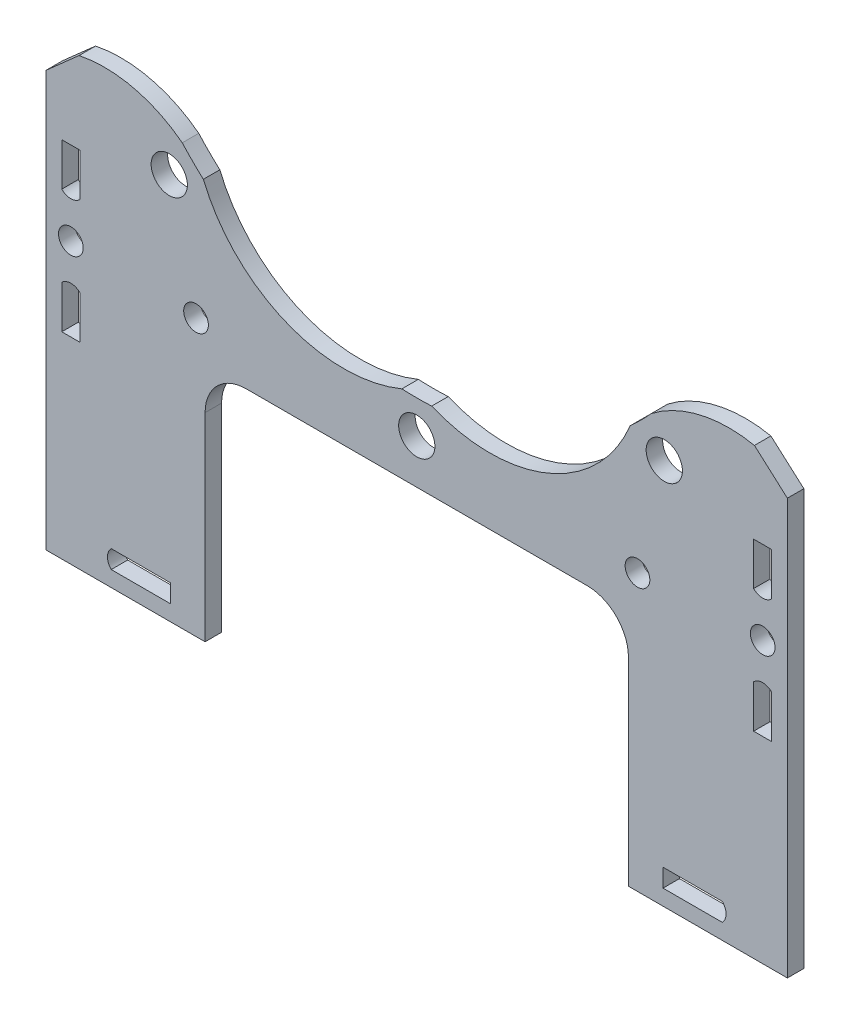
SolidWorks part; units mm, degrees
ref_plane "前视基准面" through (0, 0, 0) normal (0, 0, 1) x (1, 0, 0)
ref_plane "上视基准面" through (0, 0, 0) normal (0, 1, 0) x (1, 0, 0)
ref_plane "右视基准面" through (0, 0, 0) normal (1, 0, 0) x (0, 0, -1)
sketch "草图3" plane through (0, 0, 0) normal (0, 0, 1) x (1, 0, 0)
  line L0 (-37, -21.9902) -> (-37, -22.0902) construction
  line L2 (-41, -23.9902) -> (-42, -23.9902)
  line L5 (-37, -19.9902) -> (-30, -19.9902) construction
  line L6 (-37, -19.9902) -> (-37, -21.9902) construction
  line L7 (-37, -21.9902) -> (-30, -21.9902) construction
  line L8 (-30, -19.9902) -> (-30, -21.9902) construction
  line L9 (-37, -22.0902) -> (-37.1, -22.0902) construction
  line L11 (30, -19.9902) -> (37, -19.9902) construction
  line L12 (30, -19.9902) -> (30, -21.9902) construction
  line L13 (30, -21.9902) -> (37, -21.9902) construction
  line L14 (37, -19.9902) -> (37, -21.9902) construction
  line L19 (-37.1, -22.0902) -> (-29.9, -22.0902)
  line L21 (-37.1, -19.8902) -> (-29.9, -19.8902)
  line L22 (-29.9, -22.0902) -> (-29.9, -19.8902)
  line L23 (29.9, -22.0902) -> (29.9, -19.8902)
  line L24 (37.1, -22.0902) -> (29.9, -22.0902)
  line L26 (37.1, -19.8902) -> (29.9, -19.8902)
  line L34 (-25.7, -23.9902) -> (-25.7, -19.8902)
  line L39 (-41, 0.0098) -> (-44, 0.0098) construction
  line L40 (-44, 0.0098) -> (-44, 5.0098) construction
  line L41 (-44, 5.0098) -> (-41, 5.0098) construction
  line L55 (-41, 15.0098) -> (-44, 15.0098) construction
  line L56 (-44, 15.0098) -> (-44, 20.0098) construction
  line L57 (-44, 20.0098) -> (-41, 20.0098) construction
  line L79 (-41, -23.9902) -> (-25.7, -23.9902)
  line L82 (0, 10.5098) -> (0, 5.0098) construction
  line L87 (-25.7, -19.8902) -> (-25.7, -18.8902)
  line L88 (41, -23.9902) -> (25.7, -23.9902)
  line L89 (25.7, -19.8902) -> (25.7, -18.8902)
  line L90 (25.7, -23.9902) -> (25.7, -19.8902)
  line L91 (-25.7, -18.8902) -> (25.7, -18.8902) construction
  line L97 (-42, 0.0098) -> (-42, 5.0098) construction
  line L98 (-42, 15.0098) -> (-42, 20.0098) construction
  line L100 (-43.1, 5.1098) -> (-43.1, -0.0902)
  line L101 (-43.1, -0.0902) -> (-40.9, -0.0902)
  line L102 (-40.9, 5.1098) -> (-40.9, -0.0902)
  line L103 (-43.1, 5.1098) -> (-40.9, -0.0902) construction
  line L104 (-43.1, -0.0902) -> (-40.9, 5.1098) construction
  line L106 (-43.1, 20.1098) -> (-40.9, 20.1098)
  line L107 (-43.1, 20.1098) -> (-43.1, 14.9098)
  line L109 (-40.9, 20.1098) -> (-40.9, 14.9098)
  line L110 (-43.1, 20.1098) -> (-40.9, 14.9098) construction
  line L111 (-43.1, 14.9098) -> (-40.9, 20.1098) construction
  line L114 (43.1, 14.9098) -> (40.9, 20.1098) construction
  line L115 (43.1, 20.1098) -> (40.9, 14.9098) construction
  line L116 (43.1, -0.0902) -> (40.9, 5.1098) construction
  line L117 (43.1, 5.1098) -> (40.9, -0.0902) construction
  line L118 (42, 15.0098) -> (42, 20.0098) construction
  line L119 (42, 0.0098) -> (42, 5.0098) construction
  line L120 (44, 20.0098) -> (41, 20.0098) construction
  line L121 (44, 15.0098) -> (44, 20.0098) construction
  line L122 (41, 15.0098) -> (44, 15.0098) construction
  line L123 (44, 5.0098) -> (41, 5.0098) construction
  line L124 (44, 0.0098) -> (44, 5.0098) construction
  line L125 (41, 0.0098) -> (44, 0.0098) construction
  line L126 (40.9, 20.1098) -> (40.9, 14.9098)
  line L128 (43.1, 20.1098) -> (43.1, 14.9098)
  line L129 (43.1, 20.1098) -> (40.9, 20.1098)
  line L130 (40.9, 5.1098) -> (40.9, -0.0902)
  line L131 (43.1, -0.0902) -> (40.9, -0.0902)
  line L132 (43.1, 5.1098) -> (43.1, -0.0902)
  line L134 (-42, -23.9902) -> (-44, -23.9902)
  line L135 (-44, -23.9902) -> (-45, -23.9902)
  line L137 (41, 30.0098) -> (45, 26.4631)
  line L139 (45, 15.0098) -> (45, -23.9902)
  line L142 (42, 15.0098) -> (42, 5.0098) construction
  line L143 (-44, 5.0098) -> (-44, 15.0098) construction
  line L144 (-44, 10.0098) -> (-49.7747, 10.0098) construction
  line L145 (-45, -23.9902) -> (-45, 5.0098)
  line L147 (45, 26.4631) -> (45, 15.0098)
  line L151 (-45, 26.4631) -> (-45, 15.0098)
  line L152 (-41, 30.0098) -> (-45, 26.4631)
  line L154 (-45, 15.0098) -> (-45, 5.0098)
  line L156 (41, -23.9902) -> (45, -23.9902)
  line L159 (-25.7, -18.8902) -> (-25.7, 0.1098)
  line L160 (-20.7, 5.1098) -> (20.7, 5.1098)
  line L161 (25.7, -18.8902) -> (25.7, 0.1098)
  circle A4 centre (0, 10.5098) radius 2.2
  circle A5 centre (-30.052, 22.9577) radius 2.2
  circle A11 centre (30.052, 22.9577) radius 2.2
  circle A17 centre (-26.8, 9.5098) radius 1.5
  circle A18 centre (26.8, 9.5098) radius 1.5
  arc A19 (37.1, -19.8902) -> (37.1, -22.0902) centre (36, -20.9902) cw
  arc A20 (-37.1, -22.0902) -> (-37.1, -19.8902) centre (-36, -20.9902) cw
  arc A21 (-43.1, 5.1098) -> (-40.9, 5.1098) centre (-42, 4.0098) cw
  arc A22 (-43.1, 14.9098) -> (-40.9, 14.9098) centre (-42, 16.0098) ccw
  arc A23 (40.9, 14.9098) -> (43.1, 14.9098) centre (42, 16.0098) ccw
  arc A24 (40.9, 5.1098) -> (43.1, 5.1098) centre (42, 4.0098) cw
  circle A35 centre (42, 10.0098) radius 1.5
  arc A37 (-25.9138, 24.5366) -> (-1.8118, 14.5524) centre (-8.8707, 31.5955) ccw
  arc A40 (25.9138, 24.5366) -> (1.8118, 14.5524) centre (8.8707, 31.5955) cw
  circle A41 centre (0, 53.0098) radius 38.5 construction
  arc A42 (-1.8118, 14.5524) -> (1.8118, 14.5524) centre (0, 53.0098) ccw
  circle A43 centre (-42, 10.0098) radius 1.5
  circle A46 centre (0, 53.0098) radius 42.5 construction
  arc A47 (-25.9138, 24.5366) -> (-28.4742, 27.0971) centre (0, 53.0098) cw
  arc A48 (-41, 30.0098) -> (-28.4742, 27.0971) centre (-37.9195, 14.8681) cw
  arc A49 (25.9138, 24.5366) -> (28.4742, 27.0971) centre (0, 53.0098) ccw
  arc A50 (41, 30.0098) -> (28.4742, 27.0971) centre (37.9195, 14.8681) ccw
  arc A52 (-25.7, 0.1098) -> (-20.7, 5.1098) centre (-20.7, 0.1098) cw
  arc A53 (25.7, 0.1098) -> (20.7, 5.1098) centre (20.7, 0.1098) ccw
  point P39 (-42, 2.5098)
  point P55 (-42, 17.5098)
  point P90 (42, 17.5098)
  point P91 (42, 2.5098)
  point P131 (0, 0)
  point P132 (25.7079, -18.8902)
  dimension "D2" = 5
  dimension "D3" = 5
extrude "凸台-拉伸1" add sketch "草图3" along normal blind 2
